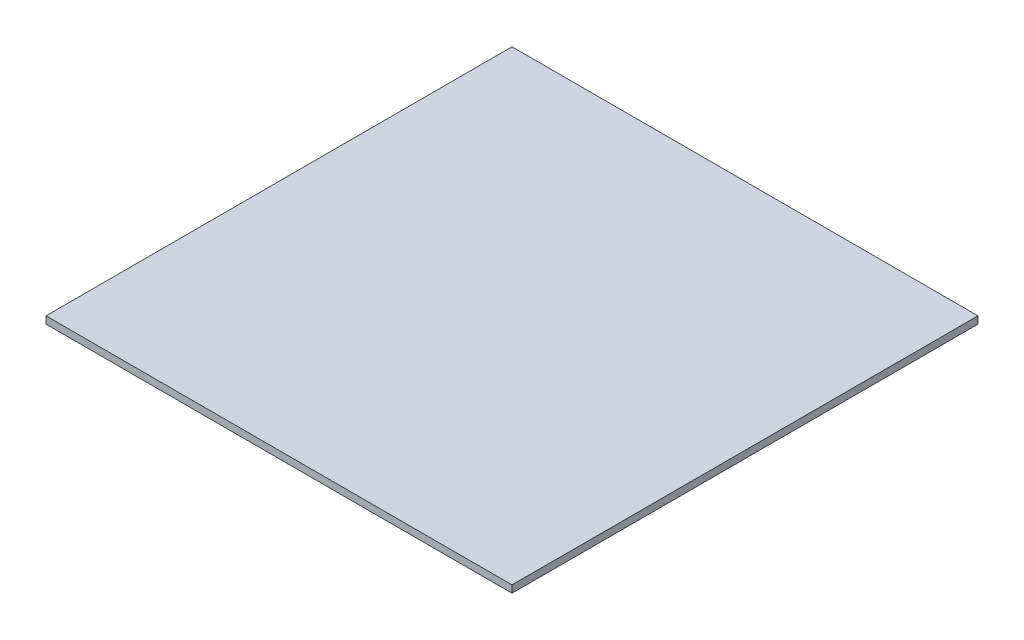
SolidWorks part; units mm, degrees
material "Wasser"
ref_plane "Ebene vorne" through (0, 0, 0) normal (0, 0, 1) x (1, 0, 0)
ref_plane "Ebene oben" through (0, 0, 0) normal (0, 1, 0) x (1, 0, 0)
ref_plane "Ebene rechts" through (0, 0, 0) normal (1, 0, 0) x (0, 0, -1)
sketch "Skizze1" plane through (0, 0, 0) normal (0, 1, 0) x (1, 0, 0)
  line L1 (-28044.5377, 452.7243) -> (1955.4623, 452.7243)
  line L2 (-28044.5377, 452.7243) -> (-28044.5377, -29547.2757)
  line L3 (-28044.5377, -29547.2757) -> (1955.4623, -29547.2757)
  line L4 (1955.4623, 452.7243) -> (1955.4623, -29547.2757)
  dimension "D1" = 30000
  dimension "D2" = 30000
extrude "Aufsatz-Linear austragen1" add sketch "Skizze1" along normal blind 466
